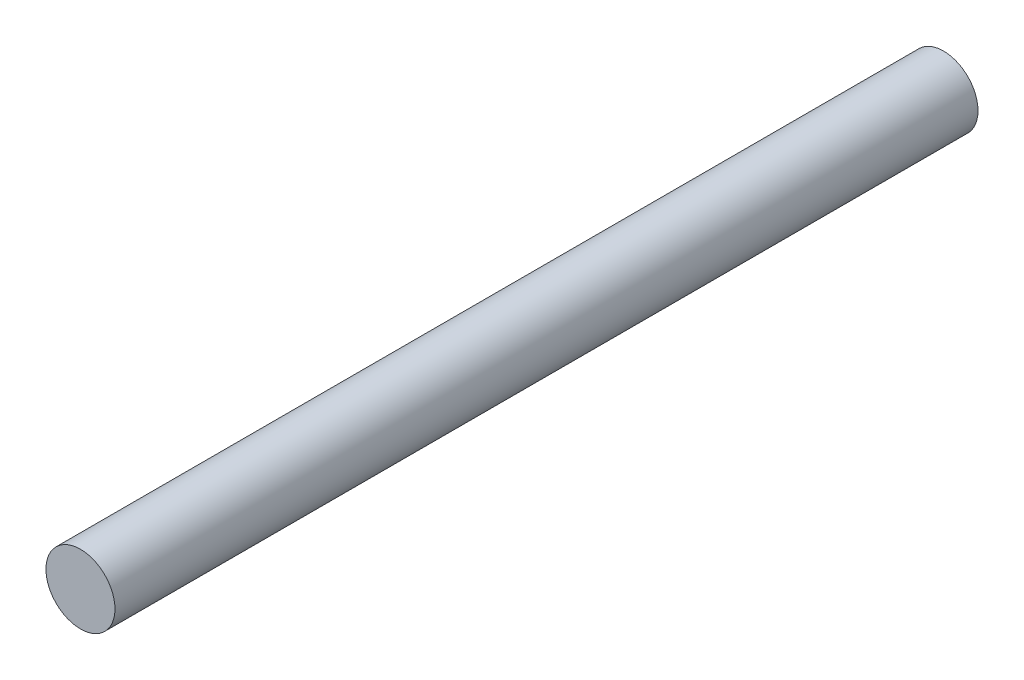
SolidWorks part; units mm, degrees
ref_plane "Alzado" through (0, 0, 0) normal (0, 0, 1) x (1, 0, 0)
ref_plane "Planta" through (0, 0, 0) normal (0, 1, 0) x (1, 0, 0)
ref_plane "Vista lateral" through (0, 0, 0) normal (1, 0, 0) x (0, 0, -1)
sketch "Croquis1" plane through (0, 0, 0) normal (0, 0, 1) x (1, 0, 0)
  circle A0 centre (0, 0) radius 7.5
  point P4 (0, 0)
  dimension "D1" = 15
extrude "Saliente-Extruir1" add sketch "Croquis1" along normal blind 187.51
